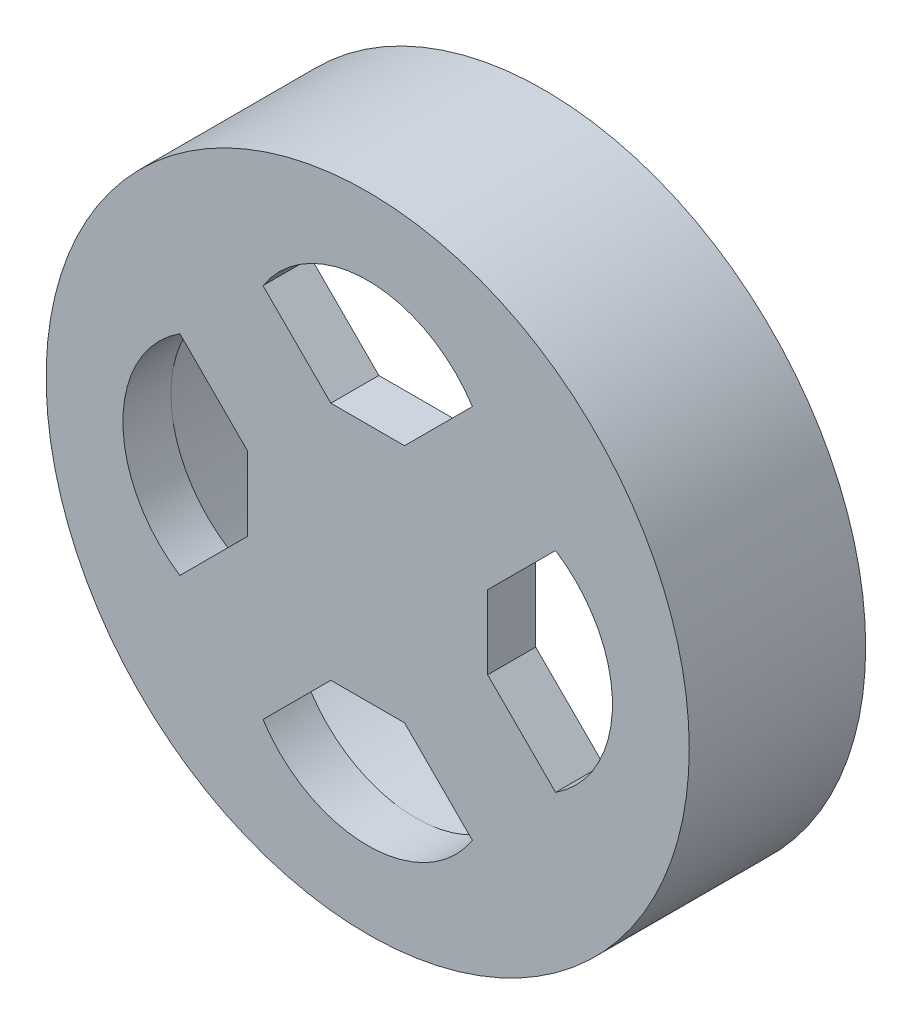
SolidWorks part; units mm, degrees
ref_plane "前视基准面" through (0, 0, 0) normal (0, 0, 1) x (1, 0, 0)
ref_plane "上视基准面" through (0, 0, 0) normal (0, 1, 0) x (1, 0, 0)
ref_plane "右视基准面" through (0, 0, 0) normal (1, 0, 0) x (0, 0, -1)
sketch "草图1" plane through (0, 0, 0) normal (0, 0, 1) x (1, 0, 0)
  circle A0 centre (0, 0) radius 33.5
  dimension "D1" = 67
extrude "凸台-拉伸1" add sketch "草图1" along normal blind 18.38
sketch "草图2" plane through (0, 0, 0) normal (0, 0, -1) x (-1, 0, 0)
  line L11 (-10.9087, 19.5711) -> (-3.8376, 12.5)
  line L12 (-3.8376, 12.5) -> (3.8376, 12.5)
  line L13 (3.8376, 12.5) -> (10.9087, 19.5711)
  line L14 (0, 0) -> (0, 41.9576) construction
  line L15 (19.5711, 10.9087) -> (12.5, 3.8376)
  line L16 (12.5, 3.8376) -> (12.5, -3.8376)
  line L17 (12.5, -3.8376) -> (19.5711, -10.9087)
  line L18 (10.9087, -19.5711) -> (3.8376, -12.5)
  line L19 (3.8376, -12.5) -> (-3.8376, -12.5)
  line L20 (-3.8376, -12.5) -> (-10.9087, -19.5711)
  line L21 (-19.5711, -10.9087) -> (-12.5, -3.8376)
  line L22 (-12.5, -3.8376) -> (-12.5, 3.8376)
  line L23 (-12.5, 3.8376) -> (-19.5711, 10.9087)
  circle A3 centre (0, 0) radius 12.5 construction
  arc A4 (-10.9087, 19.5711) -> (10.9087, 19.5711) centre (0, 12.5) cw
  arc A5 (19.5711, 10.9087) -> (19.5711, -10.9087) centre (12.5, 0) cw
  arc A6 (10.9087, -19.5711) -> (-10.9087, -19.5711) centre (0, -12.5) cw
  arc A7 (-19.5711, -10.9087) -> (-19.5711, 10.9087) centre (-12.5, 0) cw
  point P27 (0, 0)
  dimension "D1" = 25
  dimension "D2" = 13
  dimension "D3" = 10
  dimension "D4" = 135
  dimension "D5" = 4
extrude "切除-拉伸1" cut sketch "草图2" against normal blind 18.5
sketch "草图3" plane through (0, 0, 0) normal (0, 0, -1) x (-1, 0, 0)
  circle A0 centre (0, 0) radius 25.5
  arc A1 (10.9087, 19.5711) -> (-10.9087, 19.5711) centre (0, 12.5) ccw construction
  circle A2 centre (0, 0) radius 6
  dimension "D1" = 12
extrude "切除-拉伸2" cut sketch "草图3" against normal offset from surface (13.38 mm away) 5 up to face at (0, 17.5178, 18.38)
sketch "草图5" plane through (0, 0, 0) normal (0, 0, -1) x (-1, 0, 0)
  circle A0 centre (0, 0) radius 6 construction
  circle A1 centre (0, 0) radius 6
extrude "凸台-拉伸2" add sketch "草图5" along normal blind 3
sketch "草图6" plane through (0, 0, -3) normal (0, 0, -1) x (-1, 0, 0)
  line L0 (0, 0) -> (-3.3523, 0) construction
  line L1 (-1.9476, 1.87) -> (1.9476, 1.87)
  line L3 (-1.9476, -1.87) -> (1.9476, -1.87)
  arc A0 (-1.9476, 1.87) -> (-1.9476, -1.87) centre (0, 0) ccw
  arc A1 (1.9476, -1.87) -> (1.9476, 1.87) centre (0, 0) ccw
  dimension "D1" = 5.4
  dimension "D2" = 3.74
extrude "切除-拉伸3" cut sketch "草图6" against normal blind 12
